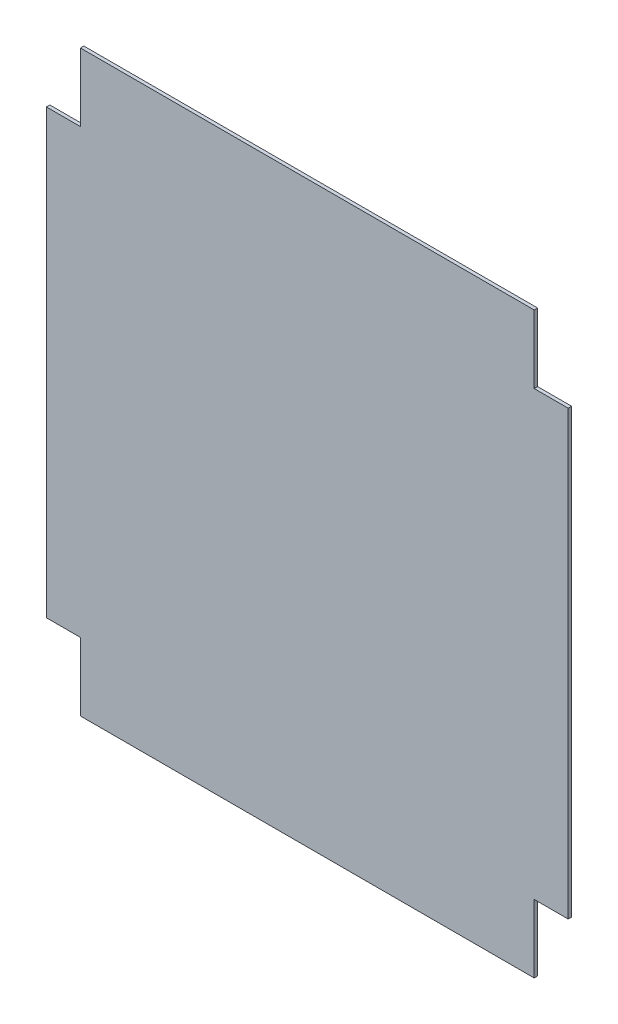
SolidWorks part; units mm, degrees
ref_plane "Přední rovina" through (0, 0, 0) normal (0, 0, 1) x (1, 0, 0)
ref_plane "Horní rovina" through (0, 0, 0) normal (0, 1, 0) x (1, 0, 0)
ref_plane "Pravá rovina" through (0, 0, 0) normal (1, 0, 0) x (0, 0, -1)
sketch "Skica1" plane through (0, 0, 0) normal (0, 0, 1) x (1, 0, 0)
  line L0 (30, 51.2163) -> (30, 111.2163)
  line L1 (30, 111.2163) -> (0, 111.2163)
  line L2 (0, 111.2163) -> (0, 501.2163)
  line L3 (0, 501.2163) -> (30, 501.2163)
  line L4 (30, 501.2163) -> (30, 561.2163)
  line L5 (30, 561.2163) -> (430, 561.2163)
  line L6 (430, 561.2163) -> (430, 501.2163)
  line L7 (430, 501.2163) -> (460, 501.2163)
  line L8 (460, 501.2163) -> (460, 111.2163)
  line L9 (460, 111.2163) -> (430, 111.2163)
  line L10 (430, 111.2163) -> (430, 51.2163)
  line L11 (430, 51.2163) -> (30, 51.2163)
  dimension "D1" = 460
  dimension "D2" = 510
  dimension "D3" = 30
  dimension "D4" = 60
extrude "Přidat vysunutím1" add sketch "Skica1" along normal blind 3
